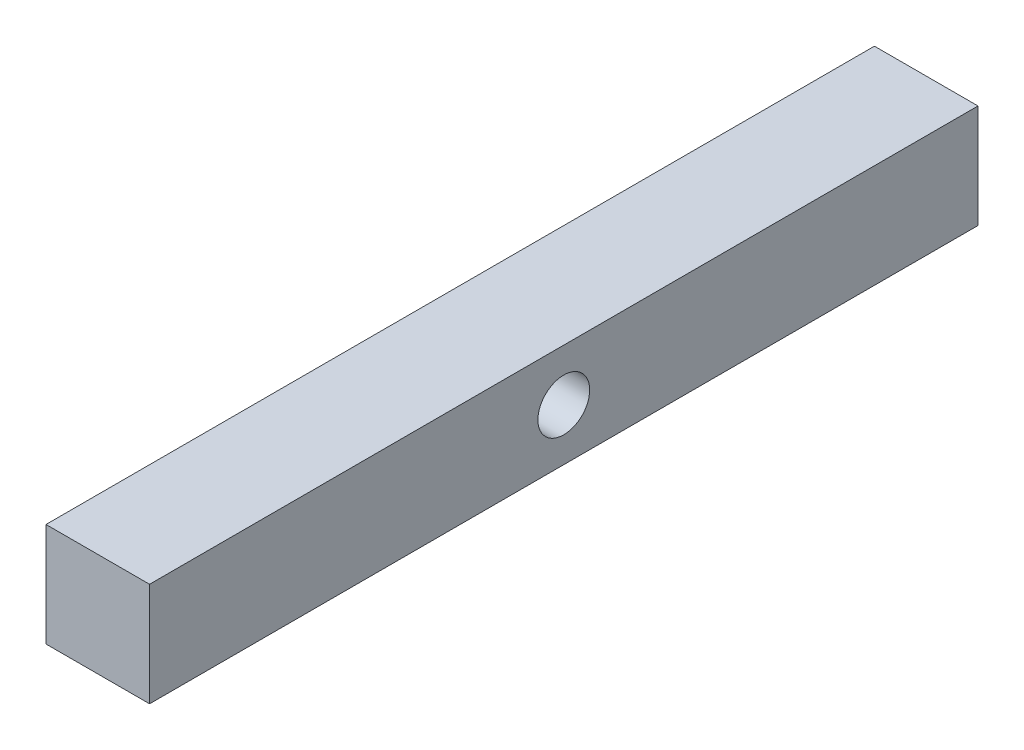
SolidWorks part; units mm, degrees
ref_plane "Front Plane" through (0, 0, 0) normal (0, 0, 1) x (1, 0, 0)
ref_plane "Top Plane" through (0, 0, 0) normal (0, 1, 0) x (1, 0, 0)
ref_plane "Right Plane" through (0, 0, 0) normal (1, 0, 0) x (0, 0, -1)
sketch "Sketch1" plane through (0, 0, 0) normal (0, 0, 1) x (1, 0, 0)
  line L1 (-20, -20) -> (20, -20)
  line L2 (-20, -20) -> (-20, 20)
  line L3 (-20, 20) -> (20, 20)
  line L4 (20, -20) -> (20, 20)
  line L5 (-20, -20) -> (20, 20) construction
  line L6 (-20, 20) -> (20, -20) construction
  point P0 (0, 0)
  dimension "D1" = 40
  dimension "D2" = 40
extrude "Boss-Extrude1" add sketch "Sketch1" along normal blind 320
sketch "Sketch3" plane through (20, 0, 0) normal (1, 0, 0) x (0, 0, -1)
  line L0 (-320, 0) -> (0, 0) construction
  line L1 (-320, -20) -> (-320, 20) construction
  circle A0 centre (-160, 0) radius 10
  dimension "D1" = 20
extrude "Cut-Extrude2" cut sketch "Sketch3" against normal blind 240
